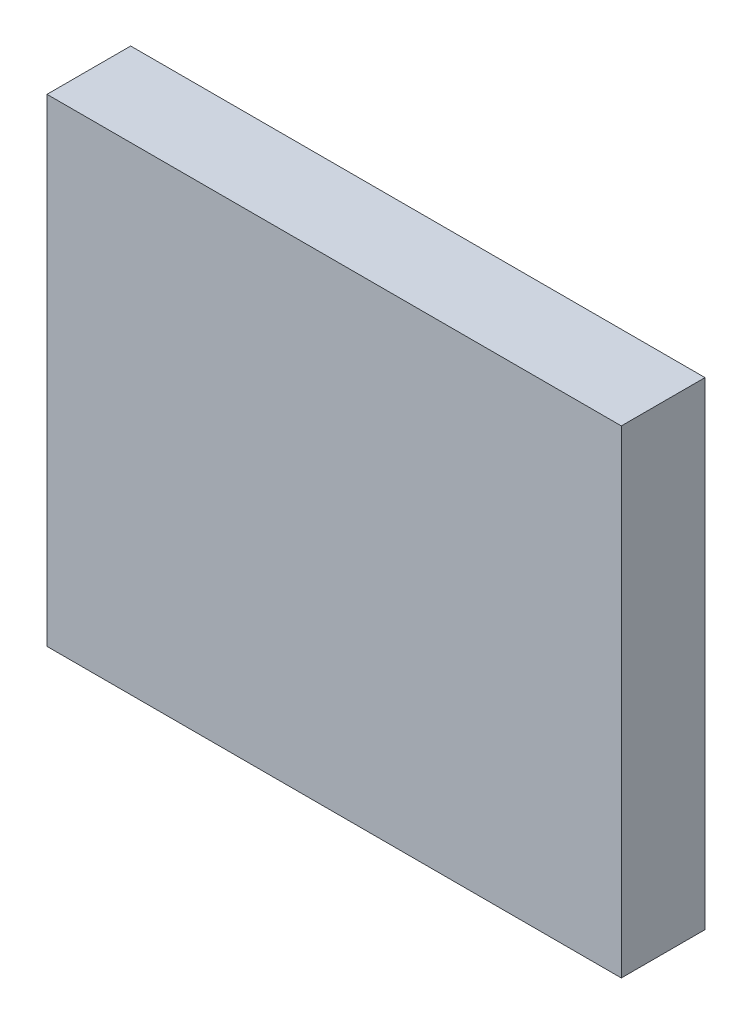
SolidWorks part; units mm, degrees
ref_plane "Front Plane" through (0, 0, 0) normal (0, 0, 1) x (1, 0, 0)
ref_plane "Top Plane" through (0, 0, 0) normal (0, 1, 0) x (1, 0, 0)
ref_plane "Right Plane" through (0, 0, 0) normal (1, 0, 0) x (0, 0, -1)
sketch "Sketch1" plane through (0, 0, 0) normal (0, 0, 1) x (1, 0, 0)
  line L0 (-3.4635, 2.75) -> (3.4, 2.75)
  line L1 (3.4, 2.75) -> (3.4, -2.964)
  line L2 (3.4, -2.964) -> (-3.4635, -2.964)
  line L3 (-3.4635, -2.964) -> (-3.4635, 2.75)
extrude "Component_Outline" add sketch "Sketch1" along normal blind 1 separate body
sketch3d "3DSketch1"
  line L0 (0, 0, 0) -> (1, 0, 0)
  line L1 (0, 0, 0) -> (0, 1, 0)
  line L2 (0, 0, 0) -> (0, 0, 1)
  point P0 (0, 0, 0)
